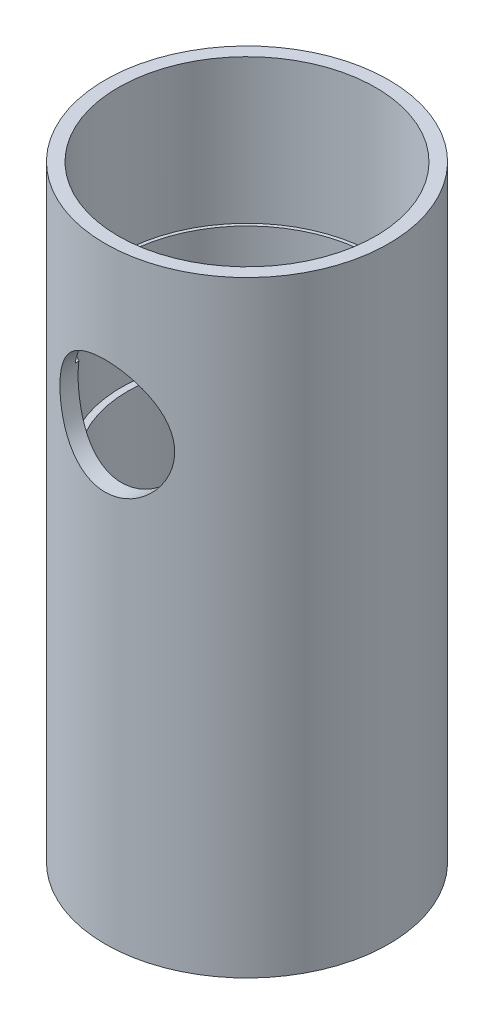
SolidWorks part; units mm, degrees
ref_plane "Front Plane" through (0, 0, 0) normal (0, 0, 1) x (1, 0, 0)
ref_plane "Top Plane" through (0, 0, 0) normal (0, 1, 0) x (1, 0, 0)
ref_plane "Right Plane" through (0, 0, 0) normal (1, 0, 0) x (0, 0, -1)
sketch "Sketch1" plane through (0, 0, 0) normal (0, 1, 0) x (1, 0, 0)
  line L0 (0, 38.25) -> (0, 43.25) construction
  circle A0 centre (0, 0) radius 38.25
  circle A1 centre (0, 0) radius 43.25
  dimension "D1" = 76.5
  dimension "D2" = 5
extrude "Boss-Extrude1" add sketch "Sketch1" along normal mid plane 185
sketch "Sketch2" plane through (0, -92.5, 0) normal (0, -1, 0) x (1, 0, 0)
  line L0 (0, 36.25) -> (0, 38.25) construction
  circle A0 centre (0, 0) radius 36.25
  circle A1 centre (0, 0) radius 38.25 construction
  circle A2 centre (0, 0) radius 38.25
  dimension "D1" = 2
extrude "Boss-Extrude2" add sketch "Sketch2" against normal blind 100 from offset 6.35 offset against normal yes
sketch "Sketch5" plane through (0, 0, 0) normal (0, 0, 1) x (1, 0, 0)
  line L0 (0, 92.5) -> (0, 44.35) construction
  line L1 (38.25, 92.5) -> (-38.25, 92.5) construction
  circle A0 centre (0, 44.35) radius 17.5
  dimension "D2" = 35
  dimension "D1" = 48.15
extrude "Cut-Extrude2" cut sketch "Sketch5" along normal through all
sketch "Sketch6" plane through (0, 92.5, 0) normal (0, 1, 0) x (1, 0, 0)
  line L0 (0, 38.25) -> (0, 39.25) construction
  circle A0 centre (0, 0) radius 39.25
  circle A1 centre (0, 0) radius 38.25 construction
  circle A2 centre (0, 0) radius 38.25
  dimension "D1" = 1
extrude "Cut-Extrude3" cut sketch "Sketch6" against normal blind 44
